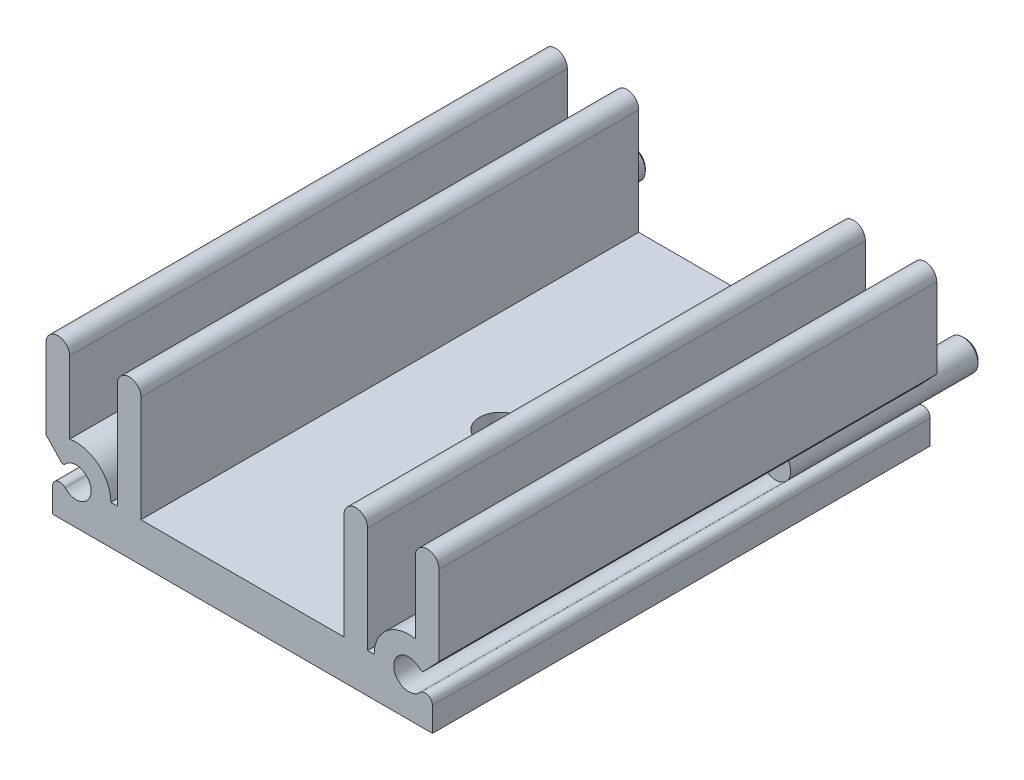
SolidWorks part; units mm, degrees
ref_plane "Front" through (0, 0, 0) normal (0, 0, 1) x (1, 0, 0)
ref_plane "Top" through (0, 0, 0) normal (0, 1, 0) x (1, 0, 0)
ref_plane "Right" through (0, 0, 0) normal (1, 0, 0) x (0, 0, -1)
sketch "Эскиз1" plane through (0, 0, 0) normal (0, 0, 1) x (1, 0, 0)
  line L0 (-14.5, -3) -> (14.5, -3)
  line L1 (14.5, -3) -> (14.5, -1.1486)
  line L2 (13.8398, 0.7753) -> (15, 2)
  line L4 (13.2, 8.1) -> (13.2, 2.6024)
  line L5 (10.05, 0) -> (9.55, 0)
  line L6 (9.55, 0) -> (9.55, 8.1)
  line L7 (7.75, 8.1) -> (7.75, 0)
  line L8 (7.75, 0) -> (-7.75, 0)
  line L10 (0, -3) -> (0, 0) construction
  line L11 (-14.5, -3) -> (-14.5, -1.1486)
  line L12 (-13.8398, 0.7753) -> (-15, 2)
  line L14 (-13.2, 8.1) -> (-13.2, 2.6024)
  line L15 (-10.05, 0) -> (-9.55, 0)
  line L16 (-9.55, 0) -> (-9.55, 8.1)
  line L17 (-7.75, 8.1) -> (-7.75, 0)
  line L18 (17.0174, 9) -> (13.7803, 9) construction
  line L19 (13.5397, -0.6) -> (15.0992, -0.6) construction
  line L20 (-15, 8.1) -> (-15, 2)
  line L21 (15, 8.1) -> (15, 2)
  line L22 (15, 2) -> (-15, 2) construction
  line L23 (0, 2) -> (0, 0) construction
  arc A0 (14.5, -1.1486) -> (13.5472, -0.7776) centre (13.9514, -1.1486) ccw
  arc A1 (13.5472, -0.7776) -> (13.5472, 0.7776) centre (12.7, 0) cw
  arc A2 (13.5472, 0.7776) -> (13.8398, 0.7753) centre (13.6946, 0.9129) ccw
  arc A3 (15, 8.1) -> (13.2, 8.1) centre (14.1, 8.1) ccw
  arc A4 (13.2, 2.6024) -> (10.05, 0) centre (12.7, 0) ccw
  arc A5 (9.55, 8.1) -> (7.75, 8.1) centre (8.65, 8.1) ccw
  arc A6 (-14.5, -1.1486) -> (-13.5472, -0.7776) centre (-13.9514, -1.1486) cw
  arc A7 (-13.5472, -0.7776) -> (-13.5472, 0.7776) centre (-12.7, 0) ccw
  arc A8 (-13.5472, 0.7776) -> (-13.8398, 0.7753) centre (-13.6946, 0.9129) cw
  arc A9 (-15, 8.1) -> (-13.2, 8.1) centre (-14.1, 8.1) cw
  arc A10 (-13.2, 2.6024) -> (-10.05, 0) centre (-12.7, 0) cw
  arc A11 (-9.55, 8.1) -> (-7.75, 8.1) centre (-8.65, 8.1) cw
  dimension "D1" = 29
  dimension "D6" = 1.15
  dimension "D10" = 0.2
  dimension "D11" = 1.5
  dimension "D2" = 12
  dimension "D3" = 3
  dimension "D4" = 15.5
  dimension "D5" = 30
  dimension "D7" = 25.4
  dimension "D8" = 2.4
  dimension "D9" = 5
  dimension "D12" = 1.8
extrude "Бобышка-Вытянуть1" add sketch "Эскиз1" along normal blind 38
sketch "Эскиз2" plane through (0, -3, 0) normal (0, -1, 0) x (1, 0, 0)
  line L0 (0, 0) -> (0, 18.3) construction
  line L1 (-14.5, 0) -> (14.5, 0) construction
  circle A0 centre (0, 18.3) radius 1.6
  dimension "D1" = 18.3
  dimension "D2" = 3.2
extrude "Вырез-Вытянуть1" cut sketch "Эскиз2" against normal up to next
sketch "Эскиз3" plane through (0, 0, 0) normal (0, 0, -1) x (-1, 0, 0)
  circle A0 centre (12.7, 0) radius 1.15
  circle A1 centre (-12.7, 0) radius 1.15
  arc A2 (-13.5472, -0.7776) -> (-13.5472, 0.7776) centre (-12.7, 0) ccw construction
  arc A3 (13.5472, 0.7776) -> (13.5472, -0.7776) centre (12.7, 0) ccw construction
extrude "Бобышка-Вытянуть2" add sketch "Эскиз3" along normal blind 4.5 and the other way blind 10
chamfer "Фаска1" distance 0.2 angle 45 2 edges at (-13.85, 0, -4.5) (11.55, 0, -4.5)
